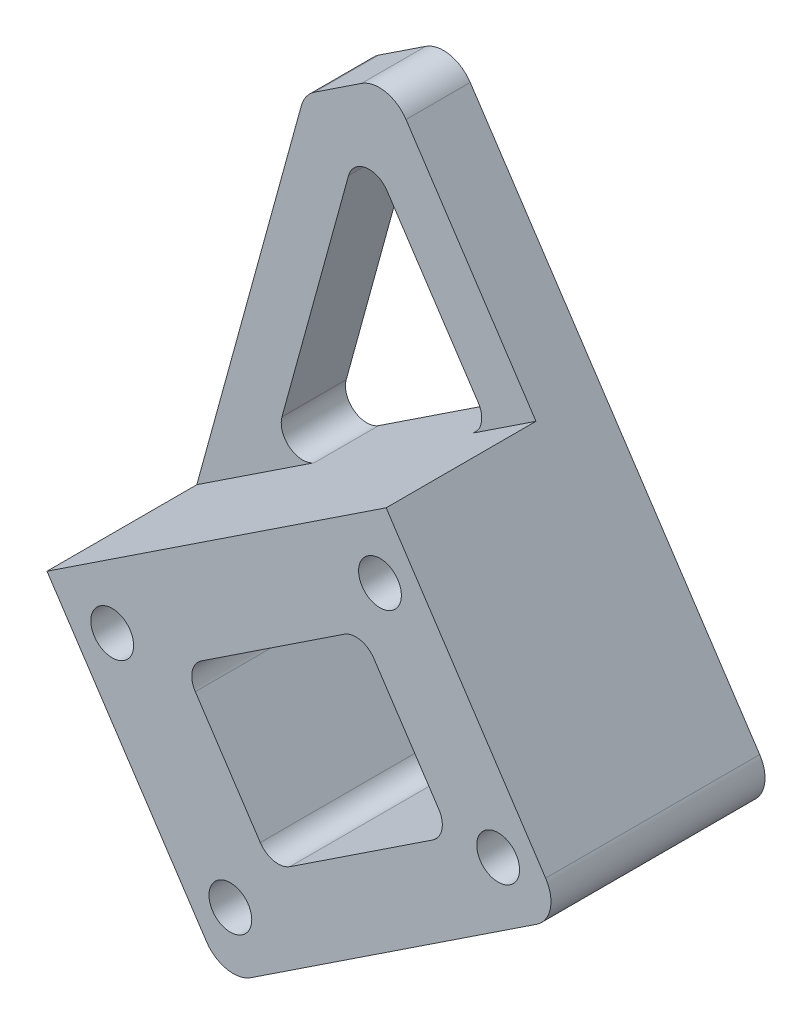
SolidWorks part; units mm, degrees
ref_plane "前视基准面" through (0, 0, 0) normal (0, 0, 1) x (1, 0, 0)
ref_plane "上视基准面" through (0, 0, 0) normal (0, 1, 0) x (1, 0, 0)
ref_plane "右视基准面" through (0, 0, 0) normal (1, 0, 0) x (0, 0, -1)
other "Configuration Table"
sketch "草图1" plane through (0, 0, 0) normal (0, 0, 1) x (1, 0, 0)
  line L0 (-13.7775, 27.1541) -> (-23.5442, -8.4021)
  line L1 (-8.1566, 31.7629) -> (-12.5405, 28.8612)
  line L2 (23.0458, -9.9434) -> (-3.9991, 30.917)
  line L3 (-4.4844, -31.7629) -> (22.2, -14.1009)
  line L4 (-23.5442, -8.4021) -> (-8.6419, -30.917)
  line L5 (-9.6859, -11.2216) -> (-3.6146, -20.3943)
  line L6 (-0.843, -20.9582) -> (12.4992, -12.1272)
  line L7 (13.0631, -9.3556) -> (6.9918, -0.1828)
  line L8 (4.2201, 0.3811) -> (-9.122, -8.4499)
  line L9 (-12.554, -1.1278) -> (2.1814, 8.6253)
  line L10 (2.7453, 11.3969) -> (-5.7751, 24.2699)
  line L11 (-9.3715, 23.6957) -> (-15.5864, 1.0697)
  arc A0 (-12.5405, 28.8612) -> (-13.7775, 27.1541) centre (-10.8847, 26.3595) ccw
  arc A1 (-3.9991, 30.917) -> (-8.1566, 31.7629) centre (-6.5008, 29.2612) ccw
  arc A2 (22.2, -14.1009) -> (23.0458, -9.9434) centre (20.5442, -11.5992) ccw
  arc A3 (-8.6419, -30.917) -> (-4.4844, -31.7629) centre (-6.1402, -29.2612) ccw
  arc A4 (20.2742, -9.3795) -> (16.9386, -11.5873) centre (18.6064, -10.4834) ccw
  arc A5 (16.9386, -11.5873) -> (20.2742, -9.3795) centre (18.6064, -10.4834) ccw
  arc A6 (-4.7424, -25.9376) -> (-8.078, -28.1454) centre (-6.4102, -27.0415) ccw
  arc A7 (-8.078, -28.1454) -> (-4.7424, -25.9376) centre (-6.4102, -27.0415) ccw
  arc A8 (-15.7812, -9.2599) -> (-19.1167, -11.4676) centre (-17.4489, -10.3638) ccw
  arc A9 (-19.1167, -11.4676) -> (-15.7812, -9.2599) centre (-17.4489, -10.3638) ccw
  arc A10 (-3.6146, -20.3943) -> (-0.843, -20.9582) centre (-1.9468, -19.2904) ccw
  arc A11 (12.4992, -12.1272) -> (13.0631, -9.3556) centre (11.3953, -10.4595) ccw
  arc A12 (6.9918, -0.1828) -> (4.2201, 0.3811) centre (5.324, -1.2867) ccw
  arc A13 (-9.122, -8.4499) -> (-9.6859, -11.2216) centre (-8.0182, -10.1177) ccw
  arc A14 (2.1814, 8.6253) -> (2.7453, 11.3969) centre (1.0775, 10.2931) ccw
  arc A15 (-5.7751, 24.2699) -> (-9.3715, 23.6957) centre (-7.4429, 23.166) ccw
  arc A16 (-15.5864, 1.0697) -> (-12.554, -1.1278) centre (-13.6578, 0.5399) ccw
  arc A17 (9.2354, 7.2982) -> (5.8999, 5.0905) centre (7.5677, 6.1943) ccw
  arc A18 (5.8999, 5.0905) -> (9.2354, 7.2982) centre (7.5677, 6.1943) ccw
extrude "凸台-拉伸1" add sketch "草图1" along normal blind 20
sketch "草图2" plane through (0, 0, 20) normal (0, 0, 1) x (1, 0, 0)
  line L0 (-23.5442, -8.4021) -> (8.1435, 12.5715)
  line L1 (23.0458, -9.9434) -> (-3.9991, 30.917) construction
  line L2 (-23.5442, -8.4021) -> (-41.4549, 18.7887)
  line L3 (-41.4549, 18.7887) -> (-3.3035, 40.2179)
  line L4 (-3.3035, 40.2179) -> (8.1435, 12.5715)
extrude "切除-拉伸1" cut sketch "草图2" against normal blind 14
